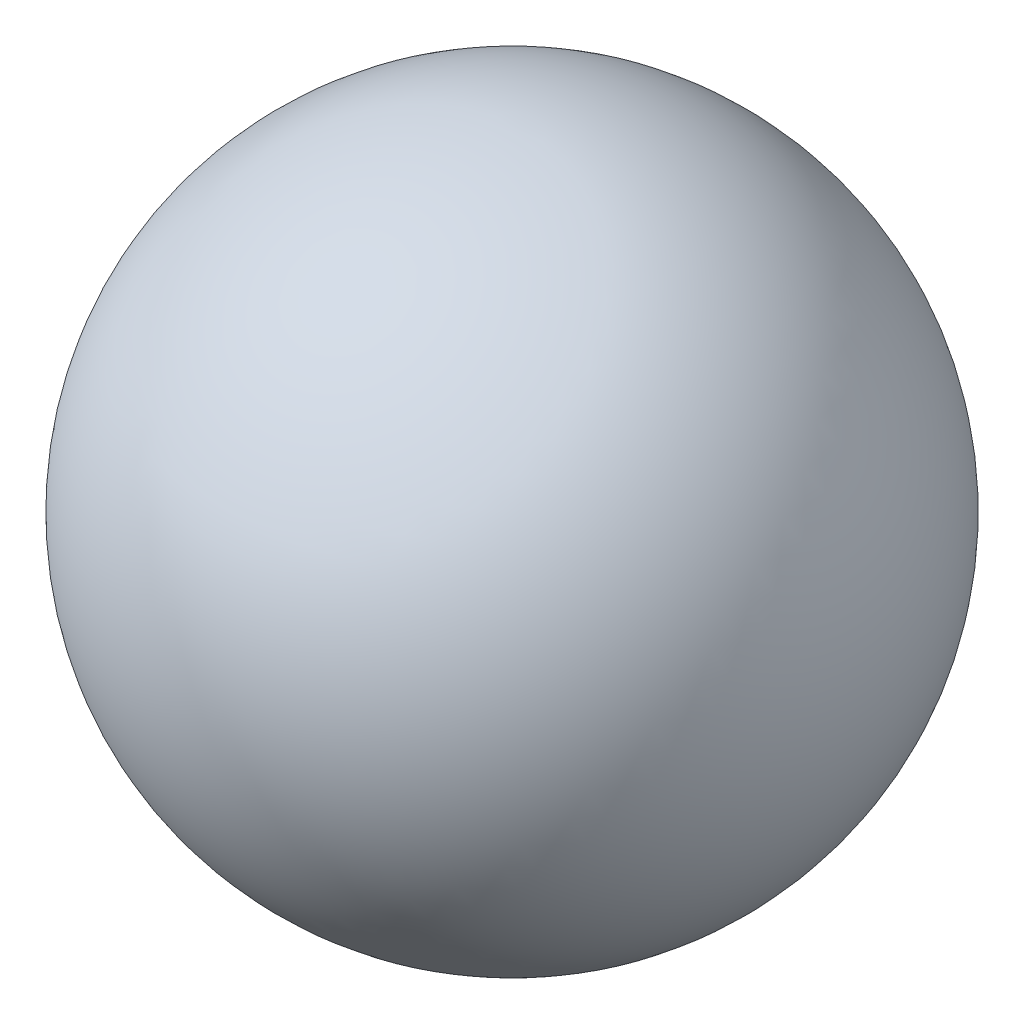
SolidWorks part; units mm, degrees
ref_plane "前视基准面" through (0, 0, 0) normal (0, 0, 1) x (1, 0, 0)
ref_plane "上视基准面" through (0, 0, 0) normal (0, 1, 0) x (1, 0, 0)
ref_plane "右视基准面" through (0, 0, 0) normal (1, 0, 0) x (0, 0, -1)
other "Configuration Table"
sketch "草图1" plane through (0, 0, 0) normal (0, 0, 1) x (1, 0, 0)
  line L0 (0, 0) -> (0, -25890.0778) construction
  line L1 (0, 7) -> (0, -7)
  arc A0 (0, 7) -> (0, -7) centre (0, 0) ccw
  dimension "D1" = 7
revolve "旋转1" add sketch "草图1" angle 360 about L0
